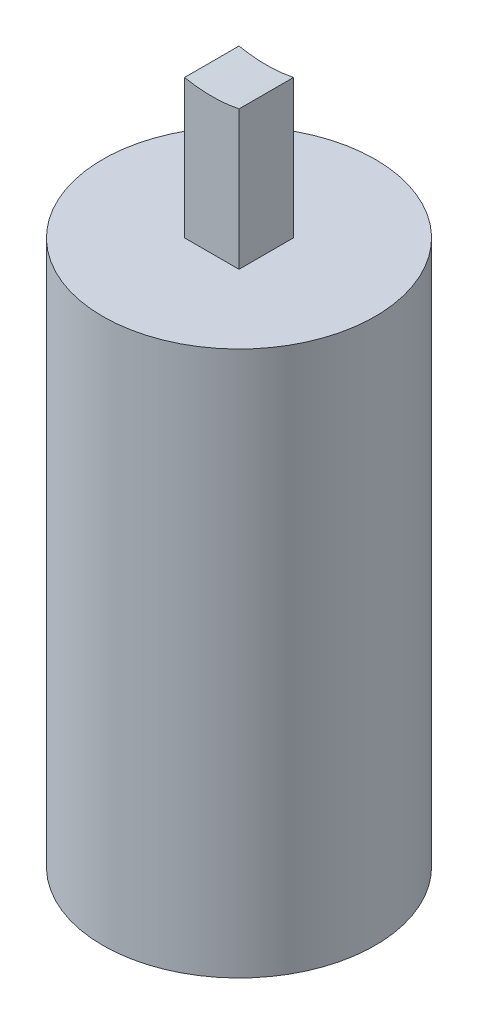
SolidWorks part; units mm, degrees
ref_plane "Front Plane" through (0, 0, 0) normal (0, 0, 1) x (1, 0, 0)
ref_plane "Top Plane" through (0, 0, 0) normal (0, 1, 0) x (1, 0, 0)
ref_plane "Right Plane" through (0, 0, 0) normal (1, 0, 0) x (0, 0, -1)
sketch "Sketch1" plane through (0, 0, 0) normal (0, 1, 0) x (1, 0, 0)
  circle A0 centre (0, 0) radius 5
  dimension "D1" = 10
extrude "Boss-Extrude1" add sketch "Sketch1" along normal blind 20
sketch "Sketch2" plane through (0, 20, 0) normal (0, 1, 0) x (1, 0, 0)
  line L1 (-1, 1) -> (1, 1)
  line L2 (-1, 1) -> (-1, -1)
  line L3 (-1, -1) -> (1, -1)
  line L4 (1, 1) -> (1, -1)
  line L5 (-1, 1) -> (1, -1) construction
  line L6 (-1, -1) -> (1, 1) construction
  point P0 (0, 0)
  dimension "D1" = 2
  dimension "D2" = 2
extrude "Boss-Extrude2" add sketch "Sketch2" along normal blind 10
sketch "Sketch3" plane through (0, 0, 1) normal (0, 0, 1) x (1, 0, 0)
  line L0 (-1, 30) -> (1, 30) construction
  circle A0 centre (0, 30) radius 5
  dimension "D1" = 10
extrude "Cut-Extrude1" cut sketch "Sketch3" against normal through all
